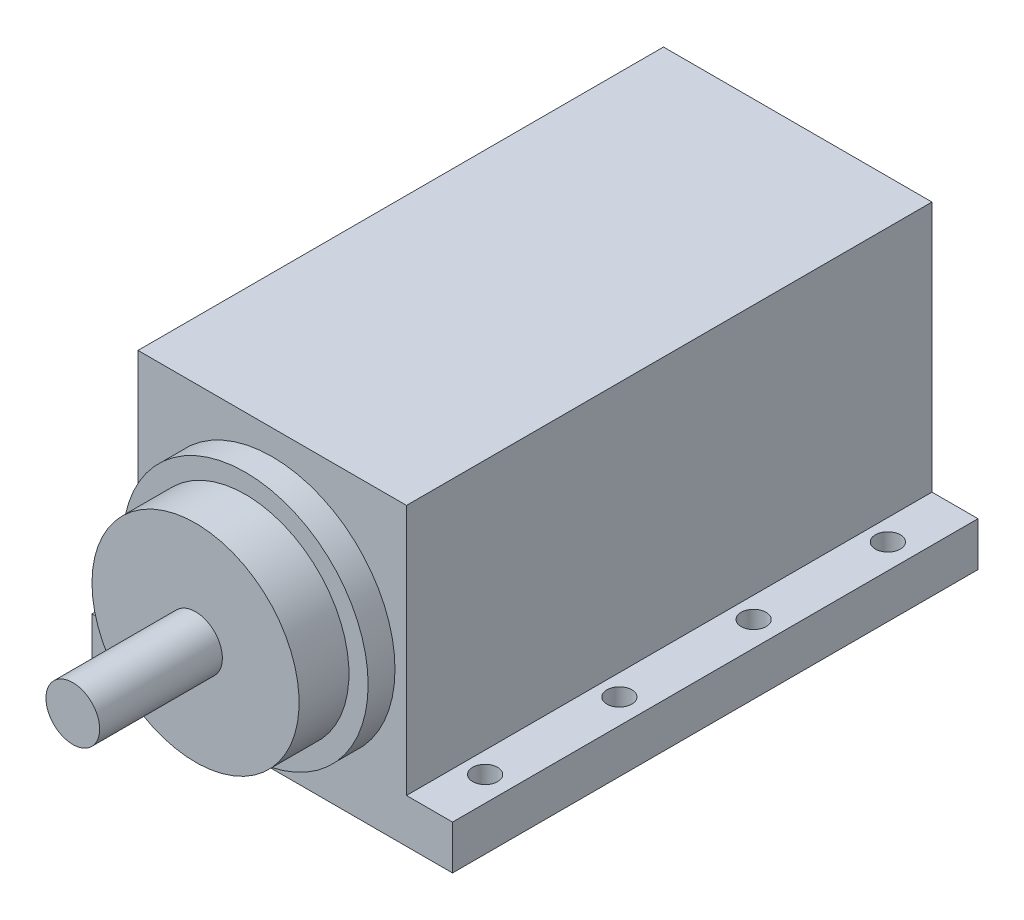
SolidWorks part; units mm, degrees
ref_plane "Plan de face" through (0, 0, 0) normal (0, 0, 1) x (1, 0, 0)
ref_plane "Plan de dessus" through (0, 0, 0) normal (0, 1, 0) x (1, 0, 0)
ref_plane "Plan de droite" through (0, 0, 0) normal (1, 0, 0) x (0, 0, -1)
sketch "Esquisse1" plane through (0, 0, 0) normal (0, 0, 1) x (1, 0, 0)
  line L0 (-47, 0) -> (47, 0)
  line L1 (47, 0) -> (47, 11.5)
  line L2 (47, 11.5) -> (35, 11.5)
  line L3 (35, 11.5) -> (35, 77)
  line L4 (35, 77) -> (-35, 77)
  line L5 (0, 77) -> (0, 0) construction
  line L6 (-35, 11.5) -> (-35, 77)
  line L7 (-47, 11.5) -> (-35, 11.5)
  line L8 (-47, 0) -> (-47, 11.5)
  dimension "D1" = 70
  dimension "D2" = 94
  dimension "D3" = 77
  dimension "D4" = 11.5
extrude "Boss.-Extru.1" add sketch "Esquisse1" along normal blind 137
sketch "Esquisse2" plane through (0, 0, 137) normal (0, 0, 1) x (1, 0, 0)
  line L0 (0, 0) -> (0, 77) construction
  line L1 (35, 77) -> (-35, 77) construction
  circle A0 centre (0, 38.5) radius 32
  dimension "D1" = 64
extrude "Boss.-Extru.2" add sketch "Esquisse2" along normal blind 7
sketch "Esquisse3" plane through (0, 0, 144) normal (0, 0, 1) x (1, 0, 0)
  circle A0 centre (0, 38.5) radius 27
  dimension "D1" = 54
extrude "Boss.-Extru.3" add sketch "Esquisse3" along normal blind 13
sketch "Esquisse4" plane through (0, 0, 157) normal (0, 0, 1) x (1, 0, 0)
  circle A0 centre (0, 38.5) radius 7
  dimension "D1" = 14
extrude "Boss.-Extru.4" add sketch "Esquisse4" along normal blind 32
sketch "Esquisse5" plane through (0, 11.5, 0) normal (0, 1, 0) x (1, 0, 0)
  line L0 (0, 0) -> (0, -137) construction
  line L1 (35, -137) -> (-35, -137) construction
  line L2 (40.5, -87) -> (40.5, -122) construction
  line L3 (-40.5, -87) -> (-40.5, -122) construction
  circle A0 centre (40.5, -122) radius 3.25
  circle A1 centre (40.5, -87) radius 3.25
  circle A2 centre (40.5, -52) radius 3.25
  circle A3 centre (40.5, -17) radius 3.25
  circle A4 centre (-40.5, -17) radius 3.25
  circle A5 centre (-40.5, -52) radius 3.25
  circle A6 centre (-40.5, -87) radius 3.25
  circle A7 centre (-40.5, -122) radius 3.25
  dimension "D1" = 15
  dimension "D2" = 81
  dimension "D3" = 6.5
  dimension "D5" = 35
  dimension "D4" = 4
extrude "Enlèv. mat.-Extru.1" cut sketch "Esquisse5" against normal through all both and the other way through all
